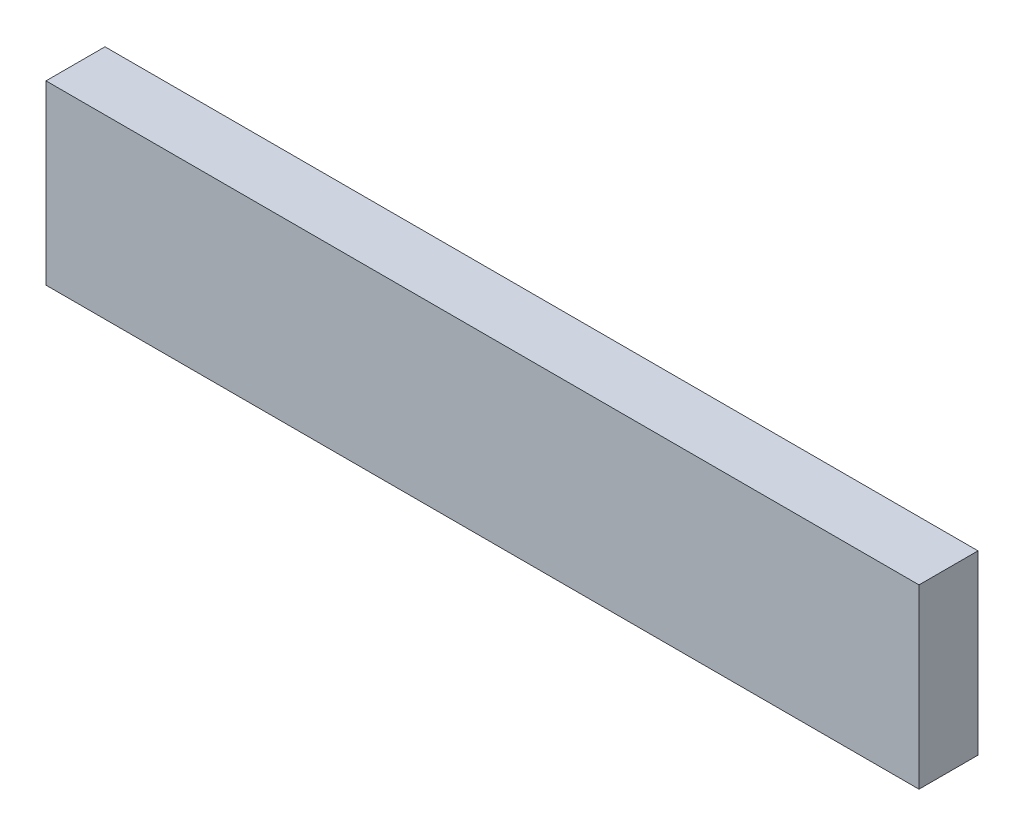
SolidWorks part; units mm, degrees
ref_plane "Front Plane" through (0, 0, 0) normal (0, 0, 1) x (1, 0, 0)
ref_plane "Top Plane" through (0, 0, 0) normal (0, 1, 0) x (1, 0, 0)
ref_plane "Right Plane" through (0, 0, 0) normal (1, 0, 0) x (0, 0, -1)
sketch "Sketch2" plane through (0, 0, 0) normal (0, 0, 1) x (1, 0, 0)
  line L1 (-37, 7.5) -> (37, 7.5)
  line L2 (-37, 7.5) -> (-37, -7.5)
  line L3 (-37, -7.5) -> (37, -7.5)
  line L4 (37, 7.5) -> (37, -7.5)
  line L5 (-37, 7.5) -> (37, -7.5) construction
  line L6 (-37, -7.5) -> (37, 7.5) construction
  point P0 (0, 0)
  dimension "D1" = 74
  dimension "D2" = 15
extrude "Boss-Extrude2" add sketch "Sketch2" along normal blind 5
